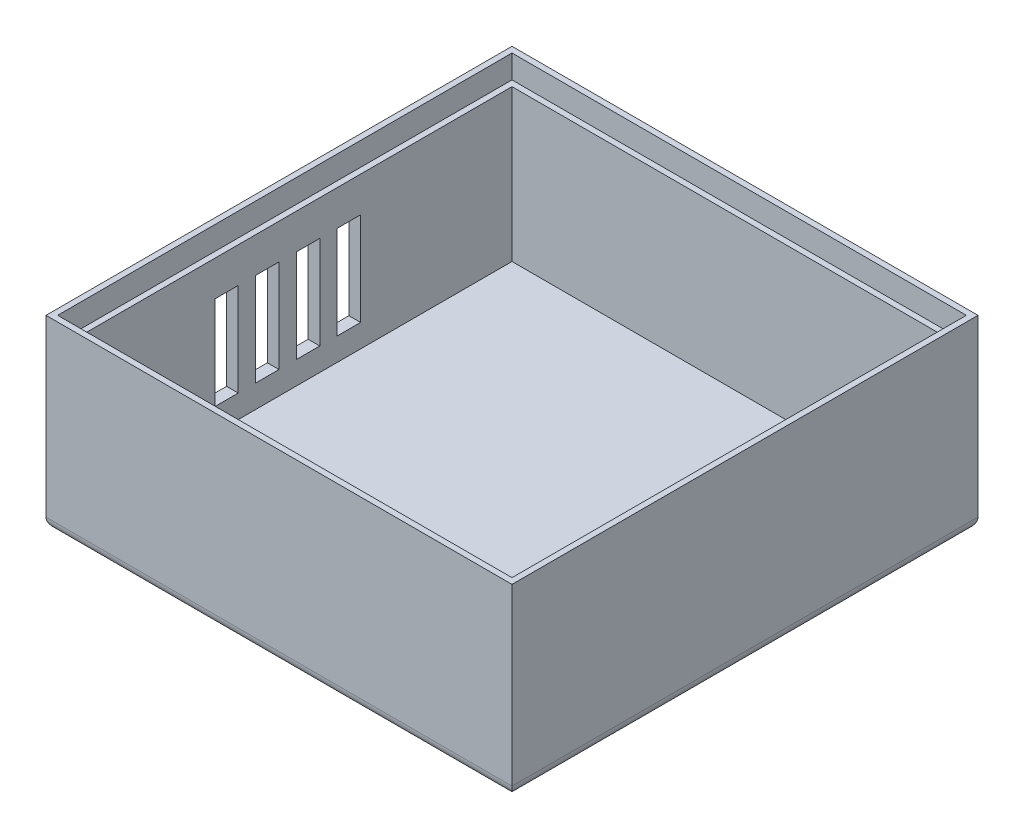
SolidWorks part; units mm, degrees
ref_plane "Front" through (0, 0, 0) normal (0, 0, 1) x (1, 0, 0)
ref_plane "Top" through (0, 0, 0) normal (0, 1, 0) x (1, 0, 0)
ref_plane "Right" through (0, 0, 0) normal (1, 0, 0) x (0, 0, -1)
sketch "Эскиз1" plane through (0, 0, 0) normal (0, 1, 0) x (1, 0, 0)
  line L1 (-1.085, 0.539) -> (38.915, 0.539)
  line L2 (-1.085, 0.539) -> (-1.085, -39.461)
  line L3 (-1.085, -39.461) -> (38.915, -39.461)
  line L4 (38.915, 0.539) -> (38.915, -39.461)
  dimension "D1" = 40
  dimension "D2" = 40
extrude "Бобышка-Вытянуть1" add sketch "Эскиз1" along normal blind 16
sketch "Эскиз2" plane through (0, 16, 0) normal (0, 1, 0) x (1, 0, 0)
  line L0 (-1.085, 0.539) -> (-1.085, -39.461) construction
  line L1 (-0.085, -0.461) -> (37.915, -0.461)
  line L2 (-0.085, -0.461) -> (-0.085, -38.461)
  line L3 (-0.085, -38.461) -> (37.915, -38.461)
  line L4 (37.915, -0.461) -> (37.915, -38.461)
  line L5 (38.915, 0.539) -> (-1.085, 0.539) construction
  dimension "D1" = 38
  dimension "D2" = 38
  dimension "D3" = 1
  dimension "D4" = 1
extrude "Вырез-Вытянуть2" cut sketch "Эскиз2" against normal blind 15
fillet "Скругление2" radius 1 4 edges at (38.915, 0, 19.461) (18.915, 0, 39.461) (-1.085, 0, 19.461) (18.915, 0, -0.539)
sketch "Эскиз5" plane through (0, 0, 38.461) normal (0, 0, -1) x (-1, 0, 0)
  line L0 (-37.915, 1) -> (-37.915, 16) construction
  line L1 (-37.915, 16) -> (0.085, 16)
  line L2 (-37.915, 16) -> (-37.915, 14)
  line L3 (-37.915, 14) -> (0.085, 14)
  line L4 (0.085, 16) -> (0.085, 14)
  line L5 (0.085, 1) -> (0.085, 16) construction
  line L6 (0.085, 16) -> (-37.915, 16) construction
  dimension "D1" = 2
  dimension "D2" = 0
extrude "Вырез-Вытянуть4" cut sketch "Эскиз5" against normal blind 0.5
sketch "Эскиз6" plane through (-0.085, 0, 0) normal (1, 0, 0) x (0, 0, -1)
  line L2 (-0.461, 16) -> (-38.961, 16)
  line L3 (-0.461, 16) -> (-0.461, 14)
  line L4 (-0.461, 14) -> (-38.961, 14)
  line L5 (-38.961, 16) -> (-38.961, 14)
  dimension "D1" = 0
  dimension "D2" = 2
extrude "Вырез-Вытянуть5" cut sketch "Эскиз6" against normal blind 0.5
sketch "Эскиз7" plane through (0, 0, 0.461) normal (0, 0, 1) x (1, 0, 0)
  line L0 (-0.585, 14) -> (-0.585, 16) construction
  line L1 (37.915, 16) -> (-0.585, 16)
  line L2 (37.915, 16) -> (37.915, 14)
  line L3 (37.915, 14) -> (-0.585, 14)
  line L4 (-0.585, 16) -> (-0.585, 14)
  dimension "D1" = 2
  dimension "D2" = 0
extrude "Вырез-Вытянуть6" cut sketch "Эскиз7" against normal blind 0.5
sketch "Эскиз8" plane through (37.915, 0, 0) normal (-1, 0, 0) x (0, 0, 1)
  line L0 (38.961, 16) -> (38.961, 14) construction
  line L1 (-0.039, 16) -> (38.961, 16)
  line L2 (-0.039, 16) -> (-0.039, 14)
  line L3 (-0.039, 14) -> (38.961, 14)
  line L4 (38.961, 16) -> (38.961, 14)
extrude "Вырез-Вытянуть7" cut sketch "Эскиз8" against normal blind 0.5
sketch "Эскиз9" plane through (-1.085, 0, 0) normal (-1, 0, 0) x (0, 0, 1)
  line L0 (16.961, 10.971) -> (16.961, 2.971)
  line L1 (13.461, 10.971) -> (15.461, 10.971)
  line L2 (13.461, 10.971) -> (13.461, 2.971)
  line L3 (13.461, 2.971) -> (15.461, 2.971)
  line L4 (15.461, 10.971) -> (15.461, 2.971)
  line L5 (16.961, 10.971) -> (18.961, 10.971)
  line L6 (18.961, 10.971) -> (18.961, 2.971)
  line L7 (16.961, 2.971) -> (18.961, 2.971)
  line L8 (20.461, 10.971) -> (20.461, 2.971)
  line L9 (20.461, 10.971) -> (22.461, 10.971)
  line L10 (22.461, 10.971) -> (22.461, 2.971)
  line L11 (20.461, 2.971) -> (22.461, 2.971)
  line L12 (23.961, 10.971) -> (23.961, 2.971)
  line L13 (23.961, 10.971) -> (25.961, 10.971)
  line L14 (25.961, 10.971) -> (25.961, 2.971)
  line L15 (23.961, 2.971) -> (25.961, 2.971)
  line L24 (-0.539, 16) -> (-0.539, 1) construction
  dimension "D1" = 2
  dimension "D2" = 8
  dimension "D4" = 1.5
  dimension "D5" = 14
  dimension "D3" = 4
extrude "Вырез-Вытянуть9" cut sketch "Эскиз9" against normal blind 10
